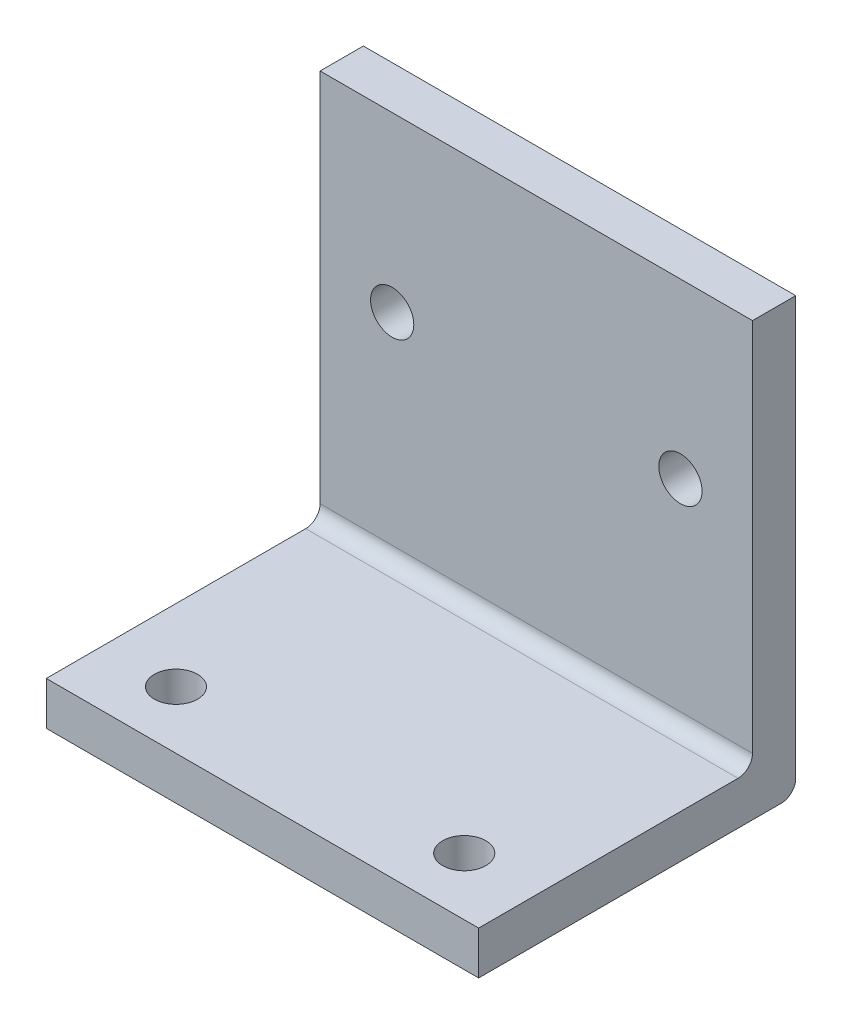
SolidWorks part; units mm, degrees
ref_plane "前视基准面" through (0, 0, 0) normal (0, 0, 1) x (1, 0, 0)
ref_plane "上视基准面" through (0, 0, 0) normal (0, 1, 0) x (1, 0, 0)
ref_plane "右视基准面" through (0, 0, 0) normal (1, 0, 0) x (0, 0, -1)
sketch "草图1" plane through (0, 0, 0) normal (0, 0, 1) x (1, 0, 0)
  line L1 (15, -15) -> (-15, -15)
  line L2 (15, -15) -> (15, 15)
  line L3 (15, 15) -> (-15, 15)
  line L4 (-15, -15) -> (-15, 15)
  line L5 (15, -15) -> (-15, 15) construction
  line L6 (15, 15) -> (-15, -15) construction
  point P0 (0, 0)
  dimension "D1" = 30
  dimension "D2" = 30
extrude "凸台-拉伸1" add sketch "草图1" along normal blind 3
sketch "草图2" plane through (0, 0, 3) normal (0, 0, 1) x (1, 0, 0)
  line L0 (0, -15) -> (0, 3) construction
  line L1 (-15, -15) -> (15, -15) construction
  circle A0 centre (10, 3) radius 1.5
  circle A1 centre (-10, 3) radius 1.5
  dimension "D2" = 10
  dimension "D3" = 3
  dimension "D5" = 3
  dimension "D1" = 18
  dimension "D4" = 10
extrude "切除-拉伸1" cut sketch "草图2" against normal blind 3.5
sketch "草图3" plane through (0, 0, 3) normal (0, 0, 1) x (1, 0, 0)
  line L0 (15, -15) -> (15, 15) construction
  line L1 (-15, -15) -> (15, -15)
  line L2 (-15, -15) -> (-15, -12)
  line L3 (-15, -12) -> (15, -12)
  line L4 (15, -15) -> (15, -12)
  dimension "D1" = 3
extrude "凸台-拉伸2" add sketch "草图3" along normal blind 27
sketch "草图4" plane through (0, -12, 0) normal (0, 1, 0) x (1, 0, 0)
  line L0 (0, -3) -> (0, -18)
  line L1 (15, -3) -> (-15, -3) construction
  circle A0 centre (-10, -18) radius 1.5
  circle A1 centre (10, -18) radius 1.5
  dimension "D2" = 10
  dimension "D4" = 3
  dimension "D5" = 3
  dimension "D1" = 15
  dimension "D3" = 10
extrude "切除-拉伸2" cut sketch "草图4" against normal blind 27 contours A1 | A0
fillet "圆角1" radius 1 1 edges at (0, -12, 3)
fillet "圆角2" radius 1 1 edges at (0, -15, 0)
sketch "草图5" plane through (0, -12, 0) normal (0, 1, 0) x (1, 0, 0)
  line L0 (15, -30) -> (15, -4) construction
  line L1 (-15, -30) -> (15, -30)
  line L2 (-15, -30) -> (-15, -22)
  line L3 (-15, -22) -> (15, -22)
  line L4 (15, -30) -> (15, -22)
  dimension "D1" = 8
extrude "切除-拉伸3" cut sketch "草图5" against normal blind 10
